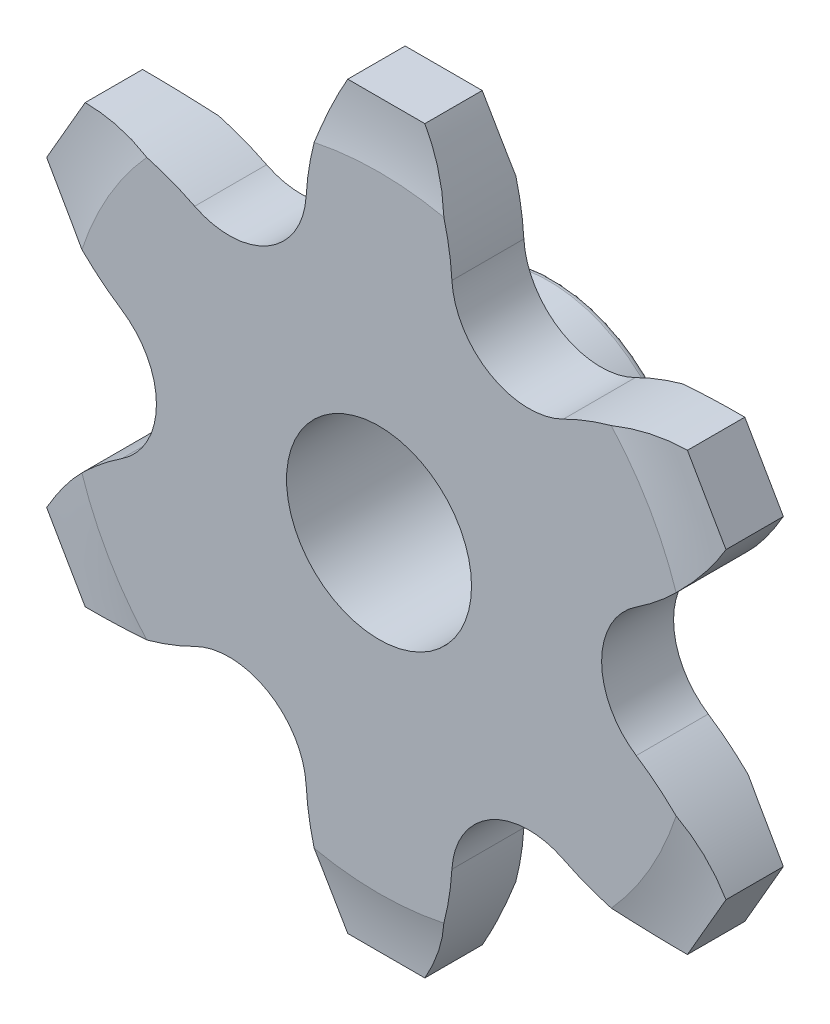
SolidWorks part; units mm, degrees
ref_plane "Front Plane" through (0, 0, 0) normal (0, 0, 1) x (1, 0, 0)
ref_plane "Top Plane" through (0, 0, 0) normal (0, 1, 0) x (1, 0, 0)
ref_plane "Right Plane" through (0, 0, 0) normal (1, 0, 0) x (0, 0, -1)
sketch "Sketch2" plane through (0, 0, 0) normal (0, 0, 1) x (1, 0, 0)
  line L0 (-12.5, 120) -> (12.5, 120)
  line L1 (0, 0) -> (0, 31.1345) construction
  line L2 (97.673, 70.8253) -> (110.173, 49.1747)
  line L3 (110.173, -49.1747) -> (97.673, -70.8253)
  line L4 (12.5, -120) -> (-12.5, -120)
  line L5 (-97.673, -70.8253) -> (-110.173, -49.1747)
  line L6 (-110.173, 49.1747) -> (-97.673, 70.8253)
  circle A0 centre (0, 0) radius 30
  arc A1 (12.5, 120) -> (23.6439, 82.6975) centre (-61.207, 77.6647) cw
  arc A2 (23.6439, 82.6975) -> (59.7962, 61.8249) centre (48.6, 84.1777) ccw
  arc A3 (-12.5, 120) -> (-23.6439, 82.6975) centre (61.207, 77.6647) ccw
  arc A4 (110.173, 49.1747) -> (83.44, 20.8725) centre (36.6561, 91.8392) cw
  arc A5 (83.44, 20.8725) -> (83.44, -20.8725) centre (97.2, 0) ccw
  arc A6 (97.673, 70.8253) -> (59.7962, 61.8249) centre (97.8631, -14.1745) ccw
  arc A7 (97.673, -70.8253) -> (59.7962, -61.8249) centre (97.8631, 14.1745) cw
  arc A8 (59.7962, -61.8249) -> (23.6439, -82.6975) centre (48.6, -84.1777) ccw
  arc A9 (110.173, -49.1747) -> (83.44, -20.8725) centre (36.6561, -91.8392) ccw
  arc A10 (-12.5, -120) -> (-23.6439, -82.6975) centre (61.207, -77.6647) cw
  arc A11 (-23.6439, -82.6975) -> (-59.7962, -61.8249) centre (-48.6, -84.1777) ccw
  arc A12 (12.5, -120) -> (23.6439, -82.6975) centre (-61.207, -77.6647) ccw
  arc A13 (-110.173, -49.1747) -> (-83.44, -20.8725) centre (-36.6561, -91.8392) cw
  arc A14 (-83.44, -20.8725) -> (-83.44, 20.8725) centre (-97.2, 0) ccw
  arc A15 (-97.673, -70.8253) -> (-59.7962, -61.8249) centre (-97.8631, 14.1745) ccw
  arc A16 (-97.673, 70.8253) -> (-59.7962, 61.8249) centre (-97.8631, -14.1745) cw
  arc A17 (-59.7962, 61.8249) -> (-23.6439, 82.6975) centre (-48.6, 84.1777) ccw
  arc A18 (-110.173, 49.1747) -> (-83.44, 20.8725) centre (-36.6561, 91.8392) ccw
  point P55 (0, 0)
  dimension "D1" = 60
  dimension "D2" = 120
  dimension "D5" = 25
  dimension "D7" = 85
  dimension "D4" = 97.2
  dimension "D6" = 25
  dimension "D3" = 6
extrude "Boss-Extrude1" add sketch "Sketch2" along normal mid plane 23.34
sketch "Sketch3" plane through (0, 0, 0) normal (1, 0, 0) x (0, 0, -1)
  line L0 (-11.67, 120) -> (-11.67, 82.6975) construction
  line L2 (-9.2988, 121.6035) -> (-9.2988, 130.8989) construction
  line L3 (-9.2988, 121.6035) -> (-9.2988, 129.4251)
  line L4 (0, 0) -> (122.9227, 0) construction
  line L5 (-9.2988, 129.4251) -> (-28.9482, 129.4251)
  line L6 (-28.9482, 129.4251) -> (-28.9482, 101.3487)
  line L7 (-28.9482, 101.3487) -> (-11.67, 101.3487)
  arc A0 (-11.67, 101.3487) -> (-9.2988, 121.6035) centre (-96.9914, 121.6035) ccw
revolve "Cut-Revolve3" cut sketch "Sketch3" angle 360 about L4
mirror "Mirror1" about plane through (0, 0, 0) normal (0, 0, 1) of "Cut-Revolve3"
sketch "Sketch4" plane through (0, 0, 11.67) normal (0, 0, 1) x (1, 0, 0)
  circle A0 centre (0, 0) radius 43.3
  circle A1 centre (0, 0) radius 30 construction
  circle A2 centre (0, 0) radius 30
  dimension "D1" = 86.6
extrude "Boss-Extrude2" add sketch "Sketch4" against normal blind 57
sketch "Sketch5" plane through (0, 0, 0) normal (1, 0, 0) x (0, 0, -1)
  line L0 (27.83, 43.3) -> (11.67, 43.3)
  line L1 (45.33, 43.3) -> (11.67, 43.3) construction
  line L2 (11.67, 31.3541) -> (11.67, 67.7877) construction
  line L3 (11.67, 43.3) -> (11.67, 52.31)
  line L4 (11.67, 59.1777) -> (11.67, 82.6975) construction
  line L5 (11.67, 52.31) -> (27.83, 43.3)
  line L6 (45.33, -43.3) -> (45.33, 43.3) construction
  line L7 (0, 0) -> (-70.2773, 0) construction
  dimension "D1" = 17.5
  dimension "D2" = 104.62
revolve "Revolve1" add sketch "Sketch5" angle 360 about L7
fillet "Fillet1" radius 2 1 edges at (43.3, 0, -45.33)
